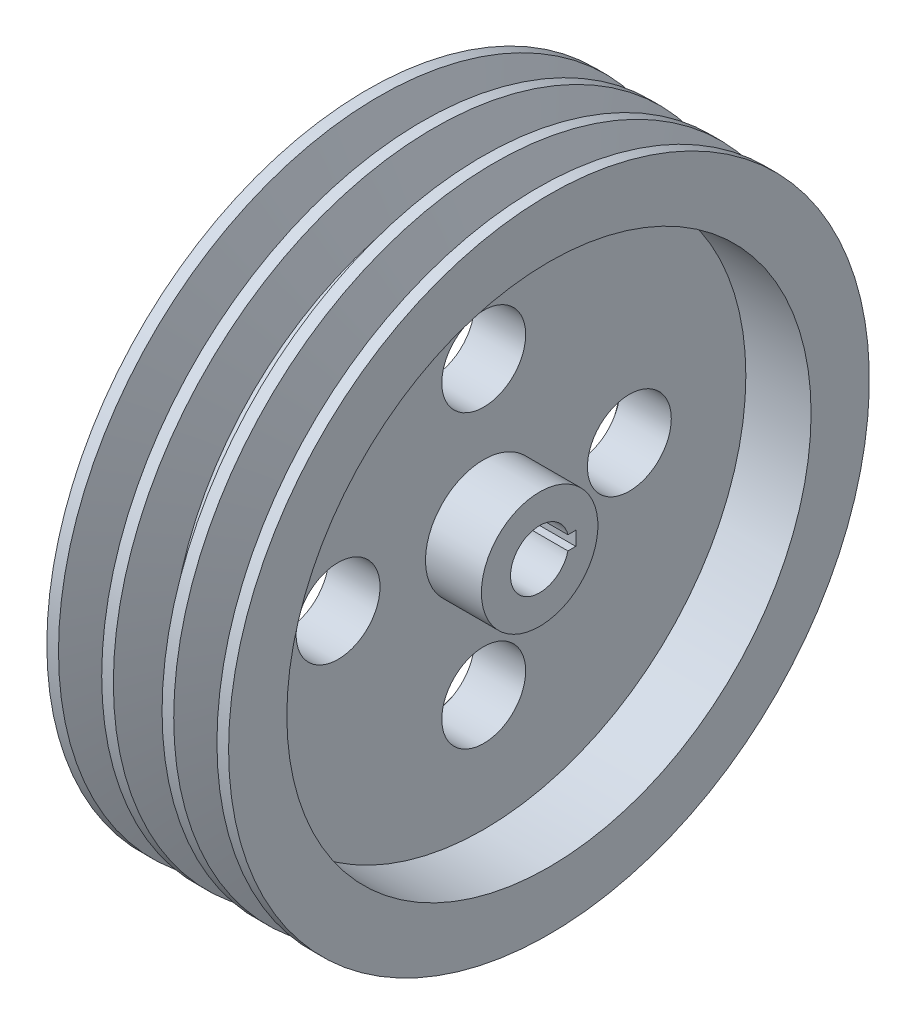
SolidWorks part; units mm, degrees
ref_plane "Front Plane" through (0, 0, 0) normal (0, 0, 1) x (1, 0, 0)
ref_plane "Top Plane" through (0, 0, 0) normal (0, 1, 0) x (1, 0, 0)
ref_plane "Right Plane" through (0, 0, 0) normal (1, 0, 0) x (0, 0, -1)
sketch "Sketch1" plane through (0, 0, 0) normal (0, 0, 1) x (1, 0, 0)
  line L0 (-35, 12.5) -> (-35, 25)
  line L1 (-35, 25) -> (-11, 25)
  line L2 (-11, 25) -> (-11, 112.5)
  line L3 (-11, 112.5) -> (-39, 112.5)
  line L4 (-39, 112.5) -> (-39, 137.5)
  line L5 (-39, 137.5) -> (-34, 137.5)
  line L6 (39, 137.5) -> (39, 112.5)
  line L7 (39, 112.5) -> (11, 112.5)
  line L8 (11, 112.5) -> (11, 25)
  line L9 (11, 25) -> (35, 25)
  line L10 (35, 25) -> (35, 12.5)
  line L11 (35, 12.5) -> (-35, 12.5)
  line L12 (0, 137.5) -> (0, 0) construction
  line L13 (-35, 12.5) -> (-35, 0)
  line L14 (-35, 0) -> (35, 0) construction
  line L15 (35, 0) -> (35, 12.5)
  line L16 (-10.4523, 137.5) -> (-3.9008, 119.5)
  line L17 (39, 137.5) -> (34, 137.5)
  line L18 (34, 137.5) -> (27.4485, 119.5)
  line L19 (27.4485, 119.5) -> (22.0038, 119.5)
  line L20 (22.0038, 119.5) -> (15.4523, 137.5)
  line L21 (24.7262, 119.5) -> (24.7262, 137.5) construction
  line L22 (34, 137.5) -> (39, 137.5)
  line L23 (-39, 137.5) -> (-34, 137.5)
  line L24 (0, 119.5) -> (0, 137.5) construction
  line L25 (-22.0038, 119.5) -> (-15.4523, 137.5)
  line L26 (-27.4485, 119.5) -> (-22.0038, 119.5)
  line L27 (-34, 137.5) -> (-27.4485, 119.5)
  line L28 (39, 137.5) -> (15.4523, 137.5)
  line L29 (-3.9008, 119.5) -> (3.9008, 119.5)
  line L30 (3.9008, 119.5) -> (10.4523, 137.5)
  line L31 (-15.4523, 137.5) -> (-10.4523, 137.5)
  line L32 (10.4523, 137.5) -> (15.4523, 137.5)
  line L33 (-24.7262, 119.5) -> (-24.7262, 145.7446) construction
  point P24 (0, 119.5)
  dimension "D1" = 78
  dimension "D2" = 25
  dimension "D3" = 20
  dimension "D4" = 11
  dimension "D5" = 25
  dimension "D6" = 125
  dimension "D7" = 12.5
  dimension "D8" = 35
  dimension "D9" = 35
  dimension "D10" = 5
  dimension "D11" = 20
  dimension "D12" = 20
  dimension "D13" = 20
  dimension "D14" = 5
  dimension "D15" = 18
  dimension "D16" = 11
  dimension "D17" = 20
  dimension "D18" = 20
revolve "Revolve5" add sketch "Sketch1" angle 360 about L14
sketch "Sketch3" plane through (35, 0, 0) normal (1, 0, 0) x (0, 0, -1)
  line L4 (0, 0) -> (15.5, 0) construction
  line L5 (15.5, 3) -> (15.5, -3)
  line L6 (15.5, 3) -> (12, 3)
  line L7 (15.5, -3) -> (12, -3)
  line L8 (12, -3) -> (12, 3)
  point P2 (15.5, 0)
  dimension "D1" = 6
  dimension "D2" = 3.5
extrude "Cut-Extrude9" cut sketch "Sketch3" against normal through all
sketch "Sketch7" plane through (11, 0, 0) normal (1, 0, 0) x (0, 0, -1)
  circle A0 centre (0, 0) radius 62.5 construction
  circle A1 centre (0, 62.5) radius 18
  circle A2 centre (62.5, 0) radius 18
  circle A3 centre (0, -62.5) radius 18
  circle A4 centre (-62.5, 0) radius 18
  point P14 (0, 0)
  dimension "D1" = 125
  dimension "D2" = 36
  dimension "D3" = 4
extrude "Cut-Extrude10" cut sketch "Sketch7" against normal through all
